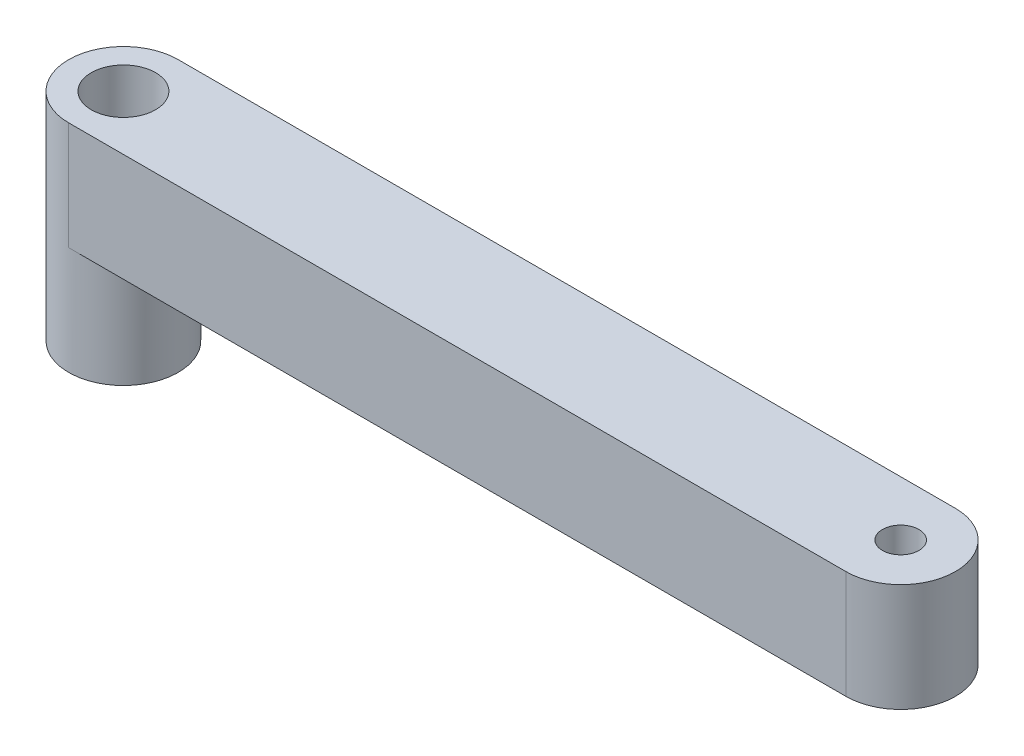
SolidWorks part; units mm, degrees
ref_plane "Front Plane" through (0, 0, 0) normal (0, 0, 1) x (1, 0, 0)
ref_plane "Top Plane" through (0, 0, 0) normal (0, 1, 0) x (1, 0, 0)
ref_plane "Right Plane" through (0, 0, 0) normal (1, 0, 0) x (0, 0, -1)
sketch "Sketch1" plane through (0, 0, 0) normal (0, 1, 0) x (1, 0, 0)
  line L1 (-17.2988, 4.646) -> (21.0552, 4.646)
  line L3 (-17.2988, -0.7579) -> (21.0552, -0.7579)
  arc A0 (-17.2988, 4.646) -> (-17.2988, -0.7579) centre (-17.2988, 1.9441) ccw
  arc A1 (21.0552, -0.7579) -> (21.0552, 4.646) centre (21.0552, 1.9441) ccw
  circle A2 centre (-17.2988, 1.9441) radius 1.5875
  circle A3 centre (21.0552, 1.9441) radius 0.9
  dimension "D1" = 38.354
extrude "Boss-Extrude1" add sketch "Sketch1" along normal blind 5.334
sketch "Sketch2" plane through (0, 0, 0) normal (0, -1, 0) x (1, 0, 0)
  circle A0 centre (-17.2988, -1.9441) radius 2.7019
  circle A1 centre (-17.2988, -1.9441) radius 1.5875
extrude "Boss-Extrude2" add sketch "Sketch2" along normal blind 5.334
